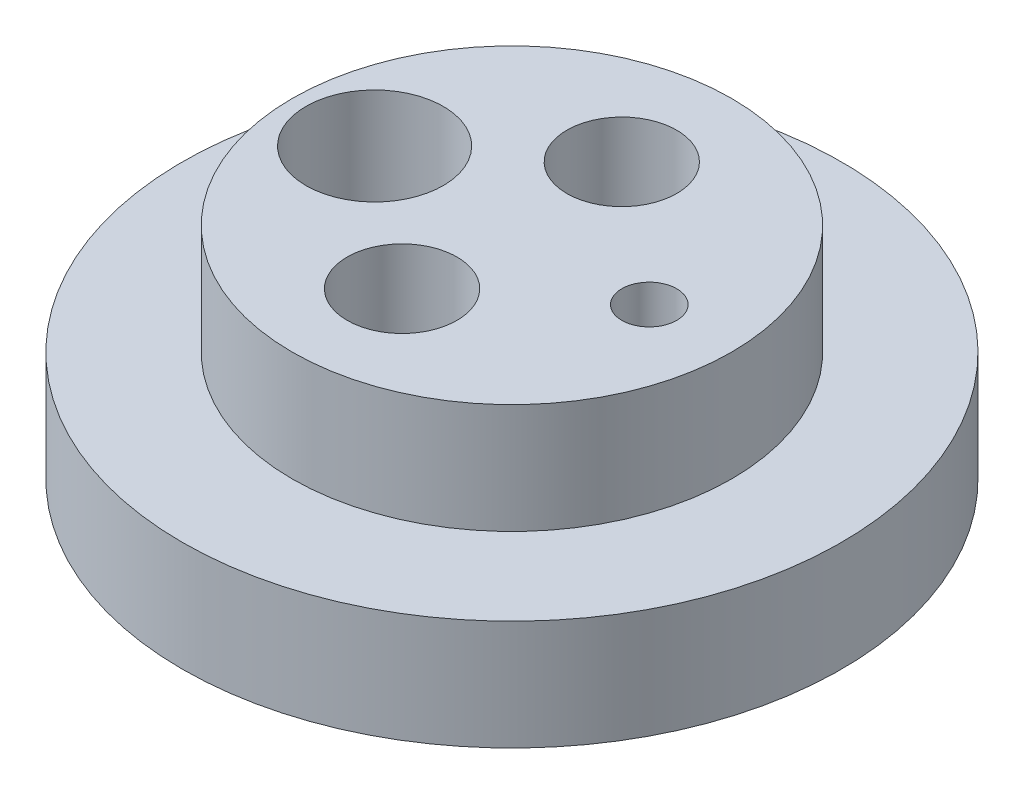
SolidWorks part; units mm, degrees
ref_plane "前视基准面" through (0, 0, 0) normal (0, 0, 1) x (1, 0, 0)
ref_plane "上视基准面" through (0, 0, 0) normal (0, 1, 0) x (1, 0, 0)
ref_plane "右视基准面" through (0, 0, 0) normal (1, 0, 0) x (0, 0, -1)
other "Configuration Table"
sketch "草图1" plane through (0, 0, 0) normal (0, 1, 0) x (1, 0, 0)
  circle A0 centre (0, 0) radius 24
  dimension "D1" = 48
extrude "凸台-拉伸1" add sketch "草图1" along normal blind 8
sketch "草图2" plane through (0, 8, 0) normal (0, 1, 0) x (1, 0, 0)
  circle A0 centre (0, 0) radius 16
  dimension "D1" = 32
extrude "凸台-拉伸2" add sketch "草图2" along normal blind 8
sketch "草图4" plane through (0, 16, 0) normal (0, 1, 0) x (1, 0, 0)
  line L0 (-16, 0) -> (16, 0) construction
  line L1 (0, 16) -> (0, -16) construction
  circle A0 centre (0, 0) radius 16 construction
  circle A1 centre (0, 0) radius 16 construction
  circle A2 centre (-10, 0) radius 5
  circle A3 centre (0, 8) radius 4
  circle A4 centre (0, -8) radius 4
  circle A5 centre (10, 0) radius 2
  dimension "D1" = 10
  dimension "D2" = 8
  dimension "D3" = 8
  dimension "D4" = 4
  dimension "D5" = 6
  dimension "D6" = 8
  dimension "D7" = 8
  dimension "D8" = 6
extrude "切除-拉伸1" cut sketch "草图4" against normal through all
